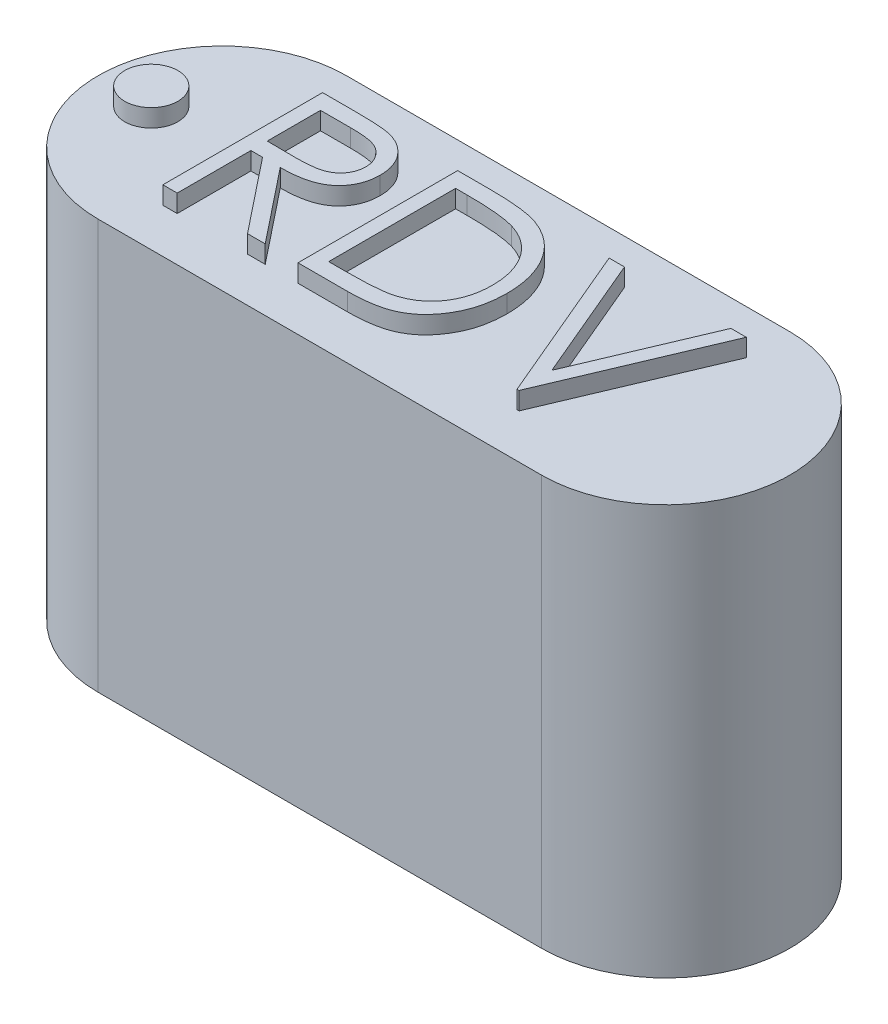
SolidWorks part; units mm, degrees
ref_plane "Front Plane" through (0, 0, 0) normal (0, 0, 1) x (1, 0, 0)
ref_plane "Top Plane" through (0, 0, 0) normal (0, 1, 0) x (1, 0, 0)
ref_plane "Right Plane" through (0, 0, 0) normal (1, 0, 0) x (0, 0, -1)
sketch "Sketch1" plane through (0, 0, 0) normal (0, 1, 0) x (1, 0, 0)
  line L0 (0, 0) -> (25, 0) construction
  line L1 (0, 7) -> (25, 7)
  line L2 (0, -7) -> (25, -7)
  line L3 (-7, 0) -> (32, 0) construction
  line L4 (0, -7) -> (0, 7) construction
  line L5 (25, -7) -> (25, 7) construction
  line L6 (0, 4.5) -> (25, 4.5) construction
  line L7 (0, -4.5) -> (25, -4.5) construction
  line L8 (12.5, 4.5) -> (12.5, -4.5) construction
  arc A0 (0, 7) -> (0, -7) centre (0, 0) ccw
  arc A1 (25, -7) -> (25, 7) centre (25, 0) ccw
  point P3 (12.5, 0)
  dimension "D2" = 7
  dimension "D1" = 25
  dimension "D5" = 2.5
  dimension "D6" = 9
extrude "Boss-Extrude1" add sketch "Sketch1" along normal blind 23.1
sketch "Sketch6" plane through (0, 23.1, 0) normal (0, 1, 0) x (1, 0, 0)
  line L0 (0, 7) -> (0, -7) construction
  line L1 (25, 7) -> (25, -7) construction
  line L2 (0, 4.5) -> (25, 4.5) construction
  line L3 (0, -4.5) -> (25, -4.5) construction
  line L4 (0, -7) -> (25, -7) construction
  text T0 "RDV" font "Century Gothic" height 9
  dimension "D1" = 9
  dimension "D2" = 2.5
extrude "Boss-Extrude3" add sketch "Sketch6" along normal blind 1
sketch "Sketch7" plane through (0, 0, 0) normal (0, -1, 0) x (1, 0, 0)
  line L0 (32, 0) -> (-7, 0) construction
  arc A0 (25, -7) -> (25, 7) centre (25, 0) ccw construction
  arc A1 (0, 7) -> (0, -7) centre (0, 0) ccw construction
  circle A2 centre (2.5, 0) radius 1.4753
  circle A3 centre (22.5, 0) radius 1.7692
  point P12 (12.5, 0)
  dimension "D1" = 10
  dimension "D2" = 10
sketch "Sketch8" plane through (0, 23.1, 0) normal (0, 1, 0) x (1, 0, 0)
  line L0 (0, 7) -> (0, -7) construction
  line L1 (-7, 0) -> (32, 0) construction
  arc A0 (0, 7) -> (0, -7) centre (0, 0) ccw construction
  arc A1 (25, -7) -> (25, 7) centre (25, 0) ccw construction
  circle A2 centre (-4, 0) radius 1.5
  point P14 (0, 0)
  dimension "D1" = 3
  dimension "D2" = 4
extrude "Boss-Extrude4" add sketch "Sketch8" along normal blind 1 contours A2
sketch "Sketch12" plane through (0, 0, 0) normal (0, -1, 0) x (1, 0, 0)
  line L0 (-7, 0) -> (32, 0) construction
sketch "Sketch14" plane through (0, 0, 0) normal (0, -1, 0) x (-1, 0, 0)
  line L0 (-32, 0) -> (7, 0) construction
  circle A0 centre (-12.5, 0) radius 3.6715
hole_wizard "M8 Tapped Hole1" positions "3DSketch4" profile "Sketch15" tap size "M8" standard "ISO"
sketch3d "3DSketch4"
  point P0 (12.5, 0, 0)
sketch "Sketch15" plane through (12.5, 0, 0) normal (1, 0, 0) x (0, 0, -1)
  line L0 (0, 0) -> (0, 15.7929)
  line L1 (0, 15.7929) -> (3.4, 13.75)
  line L2 (3.4, 13.75) -> (3.4, 0)
  line L5 (3.4, 0) -> (0, 0)
  line L10 (0, 15.7929) -> (-3.4, 13.75) construction
  line L11 (0, -6.35) -> (0, 107.95) construction
  dimension "Tap Drill Dia." = 6.8
  dimension "Tap Drill Depth" = 13.75
  dimension "Drill Angle" = 118
cosmetic thread "Hole Thread1" parameters "D1"=10, "D2"=8
hole_wizard "Ø4.0mm Dowel Hole1" positions "3DSketch5" profile "Sketch18" hole size "Ø4.0" standard "ISO"
sketch3d "3DSketch5"
  point P0 (2.5, 0, 0)
sketch "Sketch18" plane through (2.5, 0, 0) normal (1, 0, 0) x (0, 0, -1)
  line L0 (0, 0) -> (0, 16.2017)
  line L1 (0, 16.2017) -> (2, 15)
  line L2 (2, 15) -> (2, 0)
  line L5 (2, 0) -> (0, 0)
  line L10 (0, 16.2017) -> (-2, 15) construction
  line L11 (0, -6.35) -> (0, 107.95) construction
  dimension "Hole Dia." = 4
  dimension "Hole Depth" = 15
  dimension "Drill Angle" = 118
hole_wizard "Ø4.0mm Dowel Hole2" positions "3DSketch6" profile "Sketch19" hole size "Ø4.0" standard "ISO"
sketch3d "3DSketch6"
  point P0 (22.5, 0, 0)
sketch "Sketch19" plane through (22.5, 0, 0) normal (1, 0, 0) x (0, 0, -1)
  line L0 (0, 0) -> (0, 16.2017)
  line L1 (0, 16.2017) -> (2, 15)
  line L2 (2, 15) -> (2, 0)
  line L5 (2, 0) -> (0, 0)
  line L10 (0, 16.2017) -> (-2, 15) construction
  line L11 (0, -6.35) -> (0, 107.95) construction
  dimension "Hole Dia." = 4
  dimension "Hole Depth" = 15
  dimension "Drill Angle" = 118
